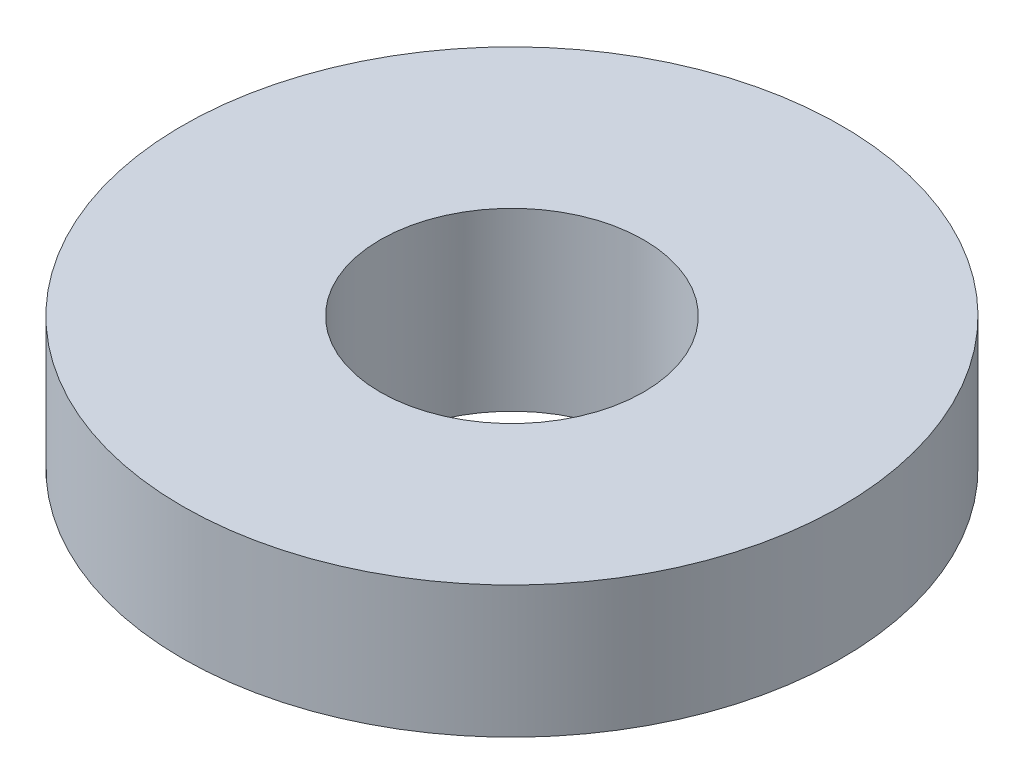
SolidWorks part; units mm, degrees
ref_plane "Front Plane" through (0, 0, 0) normal (0, 0, 1) x (1, 0, 0)
ref_plane "Top Plane" through (0, 0, 0) normal (0, 1, 0) x (1, 0, 0)
ref_plane "Right Plane" through (0, 0, 0) normal (1, 0, 0) x (0, 0, -1)
sketch "Sketch1" plane through (0, 0, 0) normal (0, 1, 0) x (1, 0, 0)
  circle A0 centre (0, 0) radius 3.75
extrude "Boss-Extrude1" add sketch "Sketch1" along normal blind 1.5
sketch "Sketch2" plane through (0, 0, 0) normal (0, -1, 0) x (1, 0, 0)
  circle A0 centre (0, 0) radius 2.5
extrude "Boss-Extrude2" add sketch "Sketch2" along normal blind 0.5
sketch "Sketch3" plane through (0, -0.5, 0) normal (0, -1, 0) x (1, 0, 0)
  circle A0 centre (0, 0) radius 1.5
extrude "Cut-Extrude1" cut sketch "Sketch3" against normal up to surface (2 mm away) up to face at (0, 1.5, 3.75)
